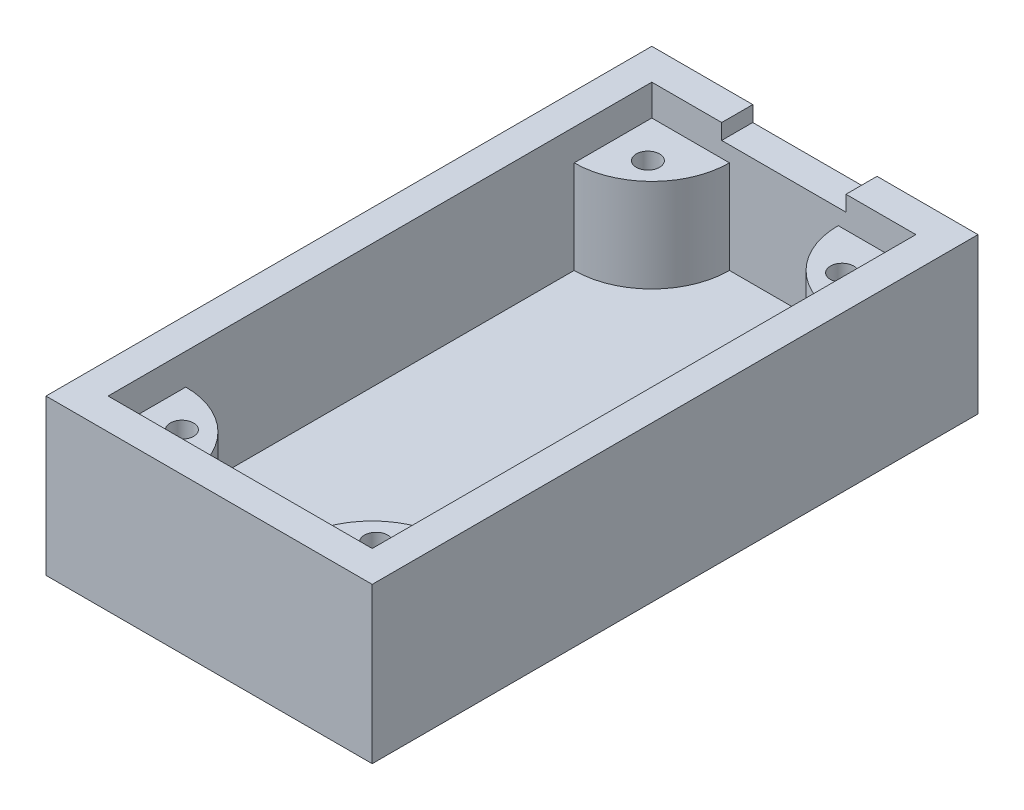
SolidWorks part; units mm, degrees
ref_plane "Front Plane" through (0, 0, 0) normal (0, 0, 1) x (1, 0, 0)
ref_plane "Top Plane" through (0, 0, 0) normal (0, 1, 0) x (1, 0, 0)
ref_plane "Right Plane" through (0, 0, 0) normal (1, 0, 0) x (0, 0, -1)
sketch "Sketch1" plane through (0, 0, 0) normal (0, 1, 0) x (1, 0, 0)
  line L1 (0, 0) -> (17, 0)
  line L2 (0, 0) -> (0, 35)
  line L3 (0, 35) -> (17, 35)
  line L4 (17, 0) -> (17, 35)
  line L5 (-2, 37) -> (19, 37)
  line L6 (-2, 37) -> (-2, -2)
  line L7 (-2, -2) -> (19, -2)
  line L8 (19, 37) -> (19, -2)
  dimension "D1" = 35
  dimension "D2" = 17
  dimension "D3" = 2
  dimension "D4" = 2
  dimension "D5" = 2
  dimension "D6" = 2
extrude "Boss-Extrude1" add sketch "Sketch1" along normal blind 8
sketch "Sketch2" plane through (0, 0, 0) normal (0, -1, 0) x (1, 0, 0)
  line L4 (-2, 2) -> (-2, -37)
  line L5 (-2, -37) -> (19, -37)
  line L6 (19, -37) -> (19, 2)
  line L7 (19, 2) -> (-2, 2)
  line L8 (-2, 2) -> (-2, -37)
  line L9 (-2, -37) -> (19, -37)
  line L10 (19, -37) -> (19, 2)
  line L11 (19, 2) -> (-2, 2)
  dimension "D1" = 0
extrude "Boss-Extrude2" add sketch "Sketch2" along normal blind 2
sketch "Sketch3" plane through (0, 0, 0) normal (0, 1, 0) x (1, 0, 0)
  line L0 (-2, -2) -> (19, -2) construction
  line L1 (14.75, 2.5) -> (2.25, 2.5) construction
  line L2 (14.75, 2.5) -> (14.75, 32.5) construction
  line L3 (14.75, 32.5) -> (12.6699, 32.5) construction
  line L4 (2.25, 2.5) -> (2.25, 32.5) construction
  line L5 (19, -2) -> (19, 37) construction
  line L6 (0, 35) -> (0, 0) construction
  line L7 (17, 35) -> (0, 35) construction
  line L8 (0, 30) -> (0, 35)
  line L9 (17, 0) -> (12, 0)
  line L10 (17, 0) -> (17, 5)
  line L11 (17, 35) -> (12, 35)
  line L12 (0, 0) -> (0, 5)
  line L13 (17, 30) -> (17, 35)
  line L14 (4.3301, 32.5) -> (2.25, 32.5) construction
  line L15 (5, 35) -> (0, 35)
  line L16 (5, 0) -> (0, 0)
  circle A0 centre (14.75, 2.5) radius 0.75
  circle A1 centre (2.25, 2.5) radius 0.75
  circle A2 centre (14.75, 32.5) radius 0.75
  circle A3 centre (2.25, 32.5) radius 0.75
  arc A4 (17, 5) -> (12, 0) centre (17, 0) ccw
  arc A5 (5, 0) -> (0, 5) centre (0, 0) ccw
  arc A6 (12, 35) -> (17, 30) centre (17, 35) ccw
  arc A7 (0, 30) -> (5, 35) centre (0, 35) ccw
  point P4 (8.5, 2.5)
  point P7 (8.5, -2)
  point P8 (14.75, 17.5)
  point P11 (19, 17.5)
  dimension "D3" = 1.5
  dimension "D4" = 1.5
  dimension "D5" = 1.5
  dimension "D6" = 1.5
  dimension "D7" = 10
  dimension "D8" = 10
  dimension "D9" = 10
  dimension "D10" = 10
  dimension "D1" = 30
  dimension "D2" = 12.5
extrude "Boss-Extrude3" add sketch "Sketch3" along normal offset from surface (6 mm away) 2 up to face at (8.5, 8, -17.5)
sketch "Sketch4" plane through (0, 0, -37) normal (0, 0, -1) x (-1, 0, 0)
  line L0 (-19, 8) -> (2, 8) construction
  line L1 (-12.5, 8) -> (-4.5, 8)
  line L2 (-12.5, 8) -> (-12.5, 7)
  line L3 (-12.5, 7) -> (-4.5, 7)
  line L4 (-4.5, 8) -> (-4.5, 7)
  line L5 (2, -2) -> (-19, -2) construction
  point P6 (-8.5, 7)
  point P9 (-8.5, -2)
  dimension "D1" = 1
  dimension "D2" = 8
extrude "Cut-Extrude1" cut sketch "Sketch4" against normal up to next
